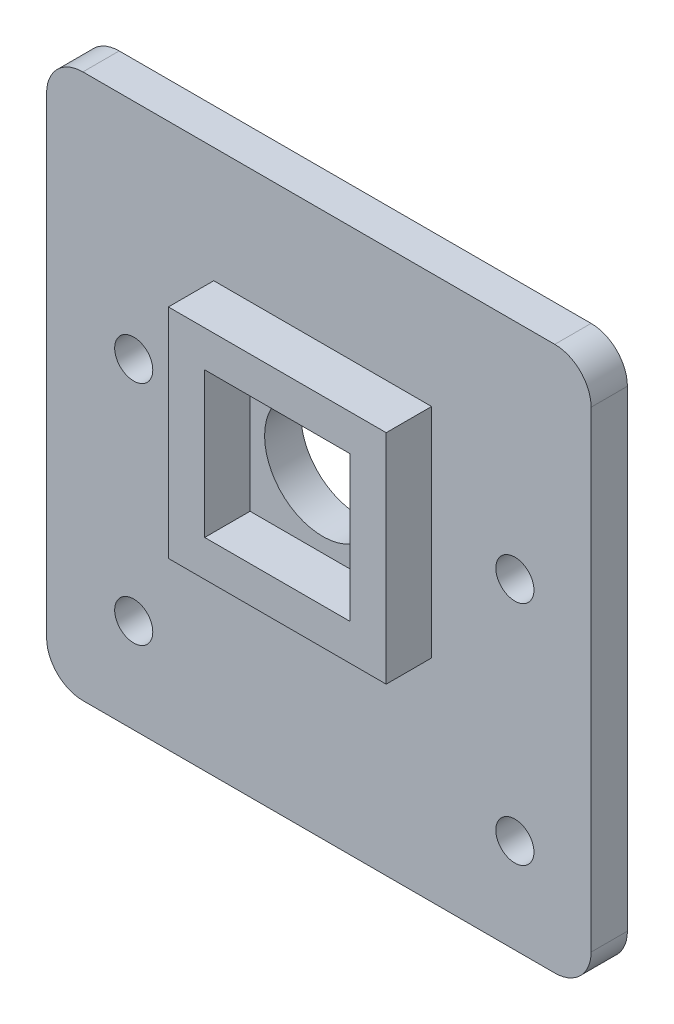
SolidWorks part; units mm, degrees
ref_plane "Front Plane" through (0, 0, 0) normal (0, 0, 1) x (1, 0, 0)
ref_plane "Top Plane" through (0, 0, 0) normal (0, 1, 0) x (1, 0, 0)
ref_plane "Right Plane" through (0, 0, 0) normal (1, 0, 0) x (0, 0, -1)
sketch "Sketch1" plane through (0, 0, 0) normal (0, 0, 1) x (1, 0, 0)
  line L1 (0, 0) -> (-30, 0)
  line L2 (0, 0) -> (0, 30)
  line L3 (0, 30) -> (-30, 30)
  line L4 (-30, 0) -> (-30, 30)
  dimension "D1" = 30
  dimension "D2" = 30
extrude "Boss-Extrude1" add sketch "Sketch1" along normal blind 2
sketch "Sketch2" plane through (0, 0, 2) normal (0, 0, 1) x (1, 0, 0)
  line L0 (-30, 30) -> (-30, 0) construction
  line L1 (-30, 0) -> (0, 0) construction
  line L2 (0, 0) -> (0, 30) construction
  circle A0 centre (-25.2, 5.199) radius 1.05
  circle A1 centre (-4.2, 5.199) radius 1.05
  circle A2 centre (-25.2, 17.699) radius 1.05
  circle A3 centre (-4.2, 17.699) radius 1.05
  dimension "D1" = 2.1
  dimension "D2" = 2.1
  dimension "D3" = 2.1
  dimension "D4" = 2.1
  dimension "D5" = 4.8
  dimension "D6" = 5.199
  dimension "D7" = 4.2
  dimension "D8" = 5.199
  dimension "D9" = 4.8
  dimension "D10" = 17.699
  dimension "D11" = 4.2
  dimension "D12" = 17.699
extrude "Cut-Extrude1" cut sketch "Sketch2" against normal blind 1.5
sketch "Sketch7" plane through (0, 0, 2) normal (0, 0, 1) x (1, 0, 0)
  line L0 (-30, 0) -> (0, 0) construction
  line L1 (-18.79, 21.64) -> (-10.79, 21.64)
  line L2 (-18.79, 21.64) -> (-18.79, 13.64)
  line L3 (-18.79, 13.64) -> (-10.79, 13.64)
  line L4 (-10.79, 21.64) -> (-10.79, 13.64)
  line L5 (-30, 30) -> (-30, 0) construction
  line L6 (-20.79, 23.64) -> (-8.79, 23.64)
  line L7 (-8.79, 23.64) -> (-8.79, 11.64)
  line L8 (-20.79, 11.64) -> (-8.79, 11.64)
  line L9 (-20.79, 23.64) -> (-20.79, 11.64)
  dimension "D1" = 8
  dimension "D2" = 8
  dimension "D3" = 13.64
  dimension "D4" = 11.21
  dimension "D5" = 2
extrude "Boss-Extrude4" add sketch "Sketch7" along normal blind 2.5
sketch "Sketch8" plane through (0, 0, 2) normal (0, 0, 1) x (1, 0, 0)
  line L0 (-30, 30) -> (-30, 0) construction
  line L4 (-18.79, 21.64) -> (-18.79, 13.64)
  line L5 (-18.79, 13.64) -> (-10.79, 13.64)
  line L6 (-10.79, 13.64) -> (-10.79, 21.64)
  line L7 (-10.79, 21.64) -> (-18.79, 21.64)
  line L8 (-18.79, 21.64) -> (-18.79, 13.64)
  line L9 (-18.79, 13.64) -> (-10.79, 13.64)
  line L10 (-10.79, 13.64) -> (-10.79, 21.64)
  line L11 (-10.79, 21.64) -> (-18.79, 21.64)
  dimension "D2" = 11.21
  dimension "D1" = 0
extrude "Cut-Extrude4" cut sketch "Sketch8" against normal blind 12.525
sketch "Sketch9" plane through (0, 0, 0) normal (0, 0, -1) x (-1, 0, 0)
  line L0 (18.79, 21.64) -> (18.79, 13.64) construction
  line L1 (10.79, 13.64) -> (10.79, 21.64) construction
  line L2 (10.79, 21.64) -> (18.79, 21.64) construction
  line L3 (18.79, 13.64) -> (10.79, 13.64) construction
  line L5 (10.79, 21.64) -> (18.79, 21.64)
  line L6 (10.79, 21.64) -> (10.79, 13.64)
  line L7 (10.79, 13.64) -> (18.79, 13.64)
  line L8 (18.79, 21.64) -> (18.79, 13.64)
  circle A0 centre (14.79, 17.64) radius 3.2
  dimension "D1" = 6.4
  dimension "D2" = 4
  dimension "D3" = 4
  dimension "D4" = 4
  dimension "D5" = 4
extrude "Boss-Extrude5" add sketch "Sketch9" against normal blind 2
fillet "Fillet1" radius 2 4 edges at (-30, 0, 1) (0, 0, 1) (0, 30, 1) (-30, 30, 1)
sketch "Sketch12" plane through (0, 0, 0) normal (0, 0, -1) x (-1, 0, 0)
  line L0 (5.5864, 22.6664) -> (5.5864, 20.7914) construction
  line L1 (5.5864, 27.3518) -> (5.5864, 28.4986) construction
  line L2 (6.0865, 26.4387) -> (6.1118, 26.4367)
  arc A0 (4.6128, 22.001) -> (4.5803, 21.522) centre (5.5864, 21.6942) ccw
  arc A1 (6.56, 22.001) -> (6.5925, 21.522) centre (5.5864, 21.6942) cw
  ellipse E0 centre (4.4059, 23.5084) end of major axis (4.9766, 24.428) minor radius 0.9345
  ellipse E1 centre (3.6535, 21.3068) end of major axis (3.0581, 22.1087) minor radius 0.5596 (3.7647, 20.5004) -> (2.9079, 21.7233) ccw
  ellipse E2 centre (7.5193, 21.3068) end of major axis (8.1147, 22.1087) minor radius 0.5596 (7.4081, 20.5004) -> (8.2649, 21.7233) cw
  ellipse E3 centre (6.7669, 23.5084) end of major axis (6.1962, 24.428) minor radius 0.9345
  spline S0 degree 3 poles (4.4661, 25.441) (4.0869, 25.541) (3.7007, 25.4582) (3.1996, 25.0648) (3.0254, 24.7187) (3.0272, 24.2593) knots 0 0 0 0 0.450332 0.550332 1 1 1 1
  spline S1 degree 2 poles (3.0272, 24.2593) (3.1067, 24.237) (3.1784, 24.2736) knots 0 0 0 1 1 1
  spline S2 degree 2 poles (4.4661, 25.441) (4.4803, 25.3569) (4.4192, 25.2998) knots 0 0 0 1 1 1
  spline S3 degree 2 poles (4.4192, 25.2998) (3.9027, 24.6623) (3.1784, 24.2736) knots 0 0 0 1 1 1
  spline S4 degree 3 poles (2.9201, 23.9593) (2.5666, 23.7576) (2.2127, 23.0851) (2.4728, 22.4495) (2.7037, 22.2258) knots 0 0 0 0 0.560262 1 1 1 1
  spline S5 degree 3 poles (2.9201, 23.9593) (2.9672, 23.98) (3.096, 23.8809) (3.1188, 23.716) (3.13, 23.6064) knots 0 0 0 0 0.260652 1 1 1 1
  spline S6 degree 3 poles (2.7037, 22.2258) (2.8317, 22.206) (2.9189, 22.3681) (2.9535, 22.4583) knots 0 0 0 0 1 1 1 1
  spline S7 degree 2 poles (3.13, 23.6064) (3.1595, 23.0141) (2.9535, 22.4583) knots 0 0 0 1 1 1
  spline S8 degree 2 poles (2.9079, 21.7233) (2.92, 20.8121) (3.7647, 20.5004) knots 0 0 0 1 1 1
  spline S9 degree 3 poles (4.6128, 22.001) (4.8153, 22.4679) (5.1862, 22.672) (5.5864, 22.6664) knots 0 0 0 0 0.49448 0.49448 0.49448 0.49448
  spline S10 degree 3 poles (4.5803, 21.522) (4.7766, 20.9634) (5.2258, 20.789) (5.5864, 20.7914) knots 0 0 0 0 0.451501 0.451501 0.451501 0.451501
  spline S11 degree 3 poles (4.5928, 20.1323) (4.6281, 20.267) (4.8215, 20.3612) (5.157, 20.4778) (5.2901, 20.4712) (5.5864, 20.4905) knots 0 0 0 0 0.33634 0.43634 1 1 1 1
  spline S12 degree 2 poles (4.5928, 20.1323) (4.5849, 20.0863) (4.6063, 20.0455) knots 0 0 0 1 1 1
  spline S13 degree 3 poles (4.6063, 20.0455) (4.7042, 19.8954) (4.8841, 19.7449) (5.1884, 19.6044) (5.375, 19.5496) (5.5864, 19.5559) knots 0 0 0 0 0.397504 0.497504 1 1 1 1
  spline S14 degree 3 poles (5.5864, 25.6921) (5.2761, 25.7126) (4.8033, 25.5166) (4.6599, 25.2139) knots 0 0 0 0 1 1 1 1
  spline S15 degree 2 poles (4.6599, 25.2139) (4.6332, 25.1127) (4.6746, 25.016) knots 0 0 0 1 1 1
  spline S16 degree 3 poles (4.6746, 25.016) (4.7203, 24.8882) (5.0275, 24.6755) (5.3683, 24.6145) (5.5864, 24.6098) knots 0 0 0 0 0.380769 1 1 1 1
  spline S17 degree 3 poles (6.4982, 25.016) (6.4525, 24.8882) (6.1453, 24.6755) (5.8045, 24.6145) (5.5864, 24.6098) knots 0 0 0 0 0.380769 1 1 1 1
  spline S18 degree 2 poles (6.5129, 25.2139) (6.5396, 25.1127) (6.4982, 25.016) knots 0 0 0 1 1 1
  spline S19 degree 3 poles (5.5864, 25.6921) (5.8967, 25.7126) (6.3695, 25.5166) (6.5129, 25.2139) knots 0 0 0 0 1 1 1 1
  spline S20 degree 3 poles (6.5665, 20.0455) (6.4686, 19.8954) (6.2887, 19.7449) (5.9844, 19.6044) (5.7978, 19.5496) (5.5864, 19.5559) knots 0 0 0 0 0.397504 0.497504 1 1 1 1
  spline S21 degree 2 poles (6.58, 20.1323) (6.5878, 20.0863) (6.5665, 20.0455) knots 0 0 0 1 1 1
  spline S22 degree 3 poles (6.58, 20.1323) (6.5447, 20.267) (6.3513, 20.3612) (6.0158, 20.4778) (5.8826, 20.4712) (5.5864, 20.4905) knots 0 0 0 0 0.33634 0.43634 1 1 1 1
  spline S23 degree 3 poles (6.5925, 21.522) (6.3962, 20.9634) (5.947, 20.789) (5.5864, 20.7914) knots 0 0 0 0 0.451501 0.451501 0.451501 0.451501
  spline S24 degree 3 poles (6.56, 22.001) (6.3575, 22.4679) (5.9866, 22.672) (5.5864, 22.6664) knots 0 0 0 0 0.49448 0.49448 0.49448 0.49448
  spline S25 degree 2 poles (8.2649, 21.7233) (8.2528, 20.8121) (7.4081, 20.5004) knots 0 0 0 1 1 1
  spline S26 degree 2 poles (8.0428, 23.6064) (8.0133, 23.0141) (8.2193, 22.4583) knots 0 0 0 1 1 1
  spline S27 degree 3 poles (8.4691, 22.2258) (8.3411, 22.206) (8.2539, 22.3681) (8.2193, 22.4583) knots 0 0 0 0 1 1 1 1
  spline S28 degree 3 poles (8.2526, 23.9593) (8.2056, 23.98) (8.0768, 23.8809) (8.054, 23.716) (8.0428, 23.6064) knots 0 0 0 0 0.260652 1 1 1 1
  spline S29 degree 3 poles (8.2526, 23.9593) (8.6062, 23.7576) (8.9601, 23.0851) (8.7, 22.4495) (8.4691, 22.2258) knots 0 0 0 0 0.560262 1 1 1 1
  spline S30 degree 2 poles (6.7536, 25.2998) (7.2701, 24.6623) (7.9944, 24.2736) knots 0 0 0 1 1 1
  spline S31 degree 2 poles (6.7067, 25.441) (6.6925, 25.3569) (6.7536, 25.2998) knots 0 0 0 1 1 1
  spline S32 degree 2 poles (8.1456, 24.2593) (8.066, 24.237) (7.9944, 24.2736) knots 0 0 0 1 1 1
  spline S33 degree 3 poles (6.7067, 25.441) (7.0859, 25.541) (7.4721, 25.4582) (7.9732, 25.0648) (8.1474, 24.7187) (8.1456, 24.2593) knots 0 0 0 0 0.450332 0.550332 1 1 1 1
  spline S34 degree 2 poles (4.4594, 19.7714) (4.9124, 19.2698) (5.5864, 19.2771) knots 0 0 0 1 1 1
  spline S35 degree 2 poles (4.4594, 19.7714) (3.9767, 19.9521) (3.5736, 20.2731) knots 0 0 0 1 1 1
  spline S36 degree 2 poles (3.5736, 20.2731) (2.7752, 20.6024) (2.6468, 21.4613) knots 0 0 0 1 1 1
  spline S37 degree 2 poles (2.6468, 21.4613) (2.497, 21.7547) (2.4415, 22.0792) knots 0 0 0 1 1 1
  spline S38 degree 3 poles (2.4415, 22.0792) (2.2134, 22.3349) (1.9009, 23.1138) (2.2811, 23.8445) (2.672, 24.1298) knots 0 0 0 0 0.443044 1 1 1 1
  spline S39 degree 3 poles (2.672, 24.1298) (2.6941, 24.185) (2.7152, 24.2148) (2.7442, 24.2537) knots 0 0 0 0 1 1 1 1
  spline S40 degree 2 poles (2.7442, 24.2537) (2.7442, 25.2242) (3.5461, 25.6386) knots 0 0 0 1 1 1
  spline S41 degree 2 poles (3.5461, 25.6386) (3.3119, 25.653) (3.2366, 25.8676) knots 0 0 0 1 1 1
  spline S42 degree 3 poles (3.2366, 25.8676) (3.0982, 25.9236) (2.9587, 25.9761) (2.9535, 26.1566) knots 0 0 0 0 1 1 1 1
  spline S43 degree 3 poles (2.9535, 26.1566) (2.7484, 26.2735) (2.727, 26.2895) (2.7122, 26.4944) knots 0 0 0 0 1 1 1 1
  spline S44 degree 2 poles (2.7122, 26.4944) (2.5063, 26.6143) (2.572, 26.811) knots 0 0 0 1 1 1
  spline S45 degree 3 poles (2.572, 26.811) (2.4868, 26.9313) (2.3857, 26.9889) (2.4773, 27.1499) knots 0 0 0 0 1 1 1 1
  spline S46 degree 2 poles (2.4773, 27.1499) (2.2981, 27.3347) (2.4691, 27.5085) knots 0 0 0 1 1 1
  spline S47 degree 3 poles (2.4691, 27.5085) (2.3555, 27.6167) (2.4238, 27.8568) (2.5808, 27.8736) knots 0 0 0 0 1 1 1 1
  spline S48 degree 2 poles (2.5808, 27.8736) (2.662, 27.8906) (2.7442, 27.8798) knots 0 0 0 1 1 1
  spline S49 degree 2 poles (2.7442, 27.8798) (2.8263, 28.0205) (2.9934, 28.008) knots 0 0 0 1 1 1
  spline S50 degree 2 poles (2.9934, 28.008) (3.0748, 28.0275) (3.1571, 28.0125) knots 0 0 0 1 1 1
  spline S51 degree 3 poles (3.1571, 28.0125) (3.2116, 28.1159) (3.346, 28.1028) (3.4398, 28.0895) knots 0 0 0 0 1 1 1 1
  spline S52 degree 3 poles (3.4398, 28.0895) (3.5458, 28.1764) (3.5906, 28.2096) (3.8177, 28.1351) knots 0 0 0 0 1 1 1 1
  spline S53 degree 2 poles (3.8177, 28.1351) (4.0116, 28.26) (4.206, 28.1192) knots 0 0 0 1 1 1
  spline S54 degree 2 poles (4.206, 28.1192) (4.3888, 28.1919) (4.5474, 28.0479) knots 0 0 0 1 1 1
  spline S55 degree 3 poles (4.5474, 28.0479) (4.7019, 28.1379) (4.8375, 28.0016) (4.9189, 27.9015) knots 0 0 0 0 1 1 1 1
  spline S56 degree 3 poles (4.9189, 27.9015) (4.9882, 27.9113) (5.0998, 27.8815) (5.2348, 27.758) (5.4564, 27.5411) (5.5864, 27.0972) knots 0 0 0 0 0.0926 0.1926 1 1 1 1
  spline S57 degree 2 poles (6.7134, 19.7714) (6.2604, 19.2698) (5.5864, 19.2771) knots 0 0 0 1 1 1
  spline S58 degree 2 poles (6.7134, 19.7714) (7.1961, 19.9521) (7.5992, 20.2731) knots 0 0 0 1 1 1
  spline S59 degree 2 poles (7.5992, 20.2731) (8.3976, 20.6024) (8.526, 21.4613) knots 0 0 0 1 1 1
  spline S60 degree 2 poles (8.526, 21.4613) (8.6758, 21.7547) (8.7313, 22.0792) knots 0 0 0 1 1 1
  spline S61 degree 3 poles (8.7313, 22.0792) (8.9594, 22.3349) (9.2719, 23.1138) (8.8917, 23.8445) (8.5008, 24.1298) knots 0 0 0 0 0.443044 1 1 1 1
  spline S62 degree 3 poles (8.5008, 24.1298) (8.4787, 24.185) (8.4576, 24.2148) (8.4286, 24.2537) knots 0 0 0 0 1 1 1 1
  spline S63 degree 2 poles (8.4286, 24.2537) (8.4286, 25.2242) (7.6267, 25.6386) knots 0 0 0 1 1 1
  spline S64 degree 2 poles (7.6267, 25.6386) (7.8609, 25.653) (7.9362, 25.8676) knots 0 0 0 1 1 1
  spline S65 degree 3 poles (6.2539, 27.9015) (6.1846, 27.9113) (6.073, 27.8815) (5.938, 27.758) (5.7164, 27.5411) (5.5864, 27.0972) knots 0 0 0 0 0.0926 0.1926 1 1 1 1
  spline S66 degree 3 poles (6.6254, 28.0479) (6.4709, 28.1379) (6.3353, 28.0016) (6.2539, 27.9015) knots 0 0 0 0 1 1 1 1
  spline S67 degree 2 poles (6.9668, 28.1192) (6.784, 28.1919) (6.6254, 28.0479) knots 0 0 0 1 1 1
  spline S68 degree 2 poles (7.3551, 28.1351) (7.1612, 28.26) (6.9668, 28.1192) knots 0 0 0 1 1 1
  spline S69 degree 3 poles (7.733, 28.0895) (7.627, 28.1764) (7.5822, 28.2096) (7.3551, 28.1351) knots 0 0 0 0 1 1 1 1
  spline S70 degree 3 poles (8.0157, 28.0125) (7.9612, 28.1159) (7.8268, 28.1028) (7.733, 28.0895) knots 0 0 0 0 1 1 1 1
  spline S71 degree 2 poles (8.1794, 28.008) (8.098, 28.0275) (8.0157, 28.0125) knots 0 0 0 1 1 1
  spline S72 degree 2 poles (8.4286, 27.8798) (8.3465, 28.0205) (8.1794, 28.008) knots 0 0 0 1 1 1
  spline S73 degree 2 poles (8.592, 27.8736) (8.5108, 27.8906) (8.4286, 27.8798) knots 0 0 0 1 1 1
  spline S74 degree 3 poles (8.7037, 27.5085) (8.8173, 27.6167) (8.749, 27.8568) (8.592, 27.8736) knots 0 0 0 0 1 1 1 1
  spline S75 degree 2 poles (8.6954, 27.1499) (8.8747, 27.3347) (8.7037, 27.5085) knots 0 0 0 1 1 1
  spline S76 degree 3 poles (8.6008, 26.811) (8.686, 26.9313) (8.7871, 26.9889) (8.6954, 27.1499) knots 0 0 0 0 1 1 1 1
  spline S77 degree 2 poles (8.4606, 26.4944) (8.6665, 26.6143) (8.6008, 26.811) knots 0 0 0 1 1 1
  spline S78 degree 3 poles (8.2193, 26.1566) (8.4243, 26.2735) (8.4458, 26.2895) (8.4606, 26.4944) knots 0 0 0 0 1 1 1 1
  spline S79 degree 3 poles (7.9362, 25.8676) (8.0746, 25.9236) (8.2141, 25.9761) (8.2193, 26.1566) knots 0 0 0 0 1 1 1 1
  spline S80 degree 2 poles (3.8083, 25.7218) (3.8837, 25.7494) (3.9286, 25.8155) knots 0 0 0 1 1 1
  spline S81 degree 2 poles (3.9286, 25.8155) (3.6928, 25.8262) (3.4711, 25.9053) knots 0 0 0 1 1 1
  spline S82 degree 2 poles (3.4711, 25.9053) (3.5527, 25.9177) (3.598, 25.9861) knots 0 0 0 1 1 1
  spline S83 degree 2 poles (3.598, 25.9861) (3.3734, 26.0212) (3.1858, 26.1477) knots 0 0 0 1 1 1
  spline S84 degree 2 poles (3.1858, 26.1477) (3.2778, 26.1432) (3.348, 26.1998) knots 0 0 0 1 1 1
  spline S85 degree 2 poles (3.348, 26.1998) (3.1237, 26.2775) (2.9481, 26.4357) knots 0 0 0 1 1 1
  spline S86 degree 2 poles (2.9481, 26.4357) (3.0367, 26.42) (3.1125, 26.4644) knots 0 0 0 1 1 1
  spline S87 degree 2 poles (3.1125, 26.4644) (2.9393, 26.5748) (2.7961, 26.7218) knots 0 0 0 1 1 1
  spline S88 degree 2 poles (2.7961, 26.7218) (2.8867, 26.7091) (2.9667, 26.7489) knots 0 0 0 1 1 1
  spline S89 degree 2 poles (2.9667, 26.7489) (2.7958, 26.8643) (2.6811, 27.0342) knots 0 0 0 1 1 1
  spline S90 degree 2 poles (2.6811, 27.0342) (2.787, 26.9982) (2.8848, 27.0455) knots 0 0 0 1 1 1
  spline S91 degree 2 poles (2.8848, 27.0455) (2.7302, 27.166) (2.6265, 27.3307) knots 0 0 0 1 1 1
  spline S92 degree 2 poles (2.6265, 27.3307) (2.716, 27.3137) (2.8058, 27.3241) knots 0 0 0 1 1 1
  spline S93 degree 2 poles (2.8058, 27.3241) (2.7639, 27.5101) (2.6322, 27.6484) knots 0 0 0 1 1 1
  spline S94 degree 2 poles (2.6322, 27.6484) (2.8417, 27.6387) (3.0506, 27.6578) knots 0 0 0 1 1 1
  spline S95 degree 2 poles (3.0506, 27.6578) (3.0066, 27.7219) (2.9441, 27.7683) knots 0 0 0 1 1 1
  spline S96 degree 2 poles (2.9441, 27.7683) (3.1707, 27.8192) (3.3933, 27.7251) knots 0 0 0 1 1 1
  spline S97 degree 3 poles (3.3933, 27.7251) (3.4746, 27.7603) (3.3577, 27.8587) (3.3251, 27.8635) knots 0 0 0 0 1 1 1 1
  spline S98 degree 2 poles (3.3251, 27.8635) (3.5263, 27.872) (3.7092, 27.7775) knots 0 0 0 1 1 1
  spline S99 degree 3 poles (3.7092, 27.7775) (3.7526, 27.8209) (3.6934, 27.869) (3.6153, 27.9407) knots 0 0 0 0 1 1 1 1
  spline S100 degree 2 poles (3.6153, 27.9407) (3.8351, 27.9183) (4.0132, 27.7914) knots 0 0 0 1 1 1
  spline S101 degree 3 poles (4.0132, 27.7914) (4.083, 27.8273) (4.0103, 27.9269) (3.9768, 27.9527) knots 0 0 0 0 1 1 1 1
  spline S102 degree 2 poles (3.9768, 27.9527) (4.1705, 27.8956) (4.3129, 27.7541) knots 0 0 0 1 1 1
  spline S103 degree 2 poles (4.3129, 27.7541) (4.3882, 27.8249) (4.3227, 27.9051) knots 0 0 0 1 1 1
  spline S104 degree 2 poles (4.3227, 27.9051) (4.479, 27.8277) (4.5803, 27.6879) knots 0 0 0 1 1 1
  spline S105 degree 3 poles (4.5803, 27.6879) (4.6378, 27.7085) (4.6585, 27.734) (4.6358, 27.8444) knots 0 0 0 0 1 1 1 1
  spline S106 degree 2 poles (4.6358, 27.8444) (4.8084, 27.7187) (4.9236, 27.5388) knots 0 0 0 1 1 1
  spline S107 degree 2 poles (4.9236, 27.5388) (4.9685, 27.5954) (4.9712, 27.6682) knots 0 0 0 1 1 1
  spline S108 degree 3 poles (4.9712, 27.6682) (5.106, 27.5678) (5.2785, 27.2989) (5.4306, 26.8212) (5.3198, 26.5497) (5.0863, 26.4387) knots 0 0 0 0 0.370607 0.596988 1 1 1 1
  spline S109 degree 1 poles (5.0863, 26.4387) (5.061, 26.4367) knots 0 0 1 1
  spline S110 degree 2 poles (5.061, 26.4367) (4.2873, 27.0507) (3.348, 27.3518) knots 0 0 0 1 1 1
  spline S111 degree 3 poles (3.348, 27.3518) (3.7184, 27.1581) (4.2685, 26.8666) (4.7453, 26.4699) (4.9377, 26.2658) knots 0 0 0 0 0.517858 1 1 1 1
  spline S112 degree 3 poles (4.9377, 26.2658) (4.9024, 26.1408) (4.7187, 25.775) (4.1062, 25.6906) (3.8083, 25.7218) knots 0 0 0 0 0.232285 1 1 1 1
  spline S113 degree 3 poles (6.2351, 26.2658) (6.2704, 26.1408) (6.4541, 25.775) (7.0666, 25.6906) (7.3645, 25.7218) knots 0 0 0 0 0.232285 1 1 1 1
  spline S114 degree 2 poles (7.3645, 25.7218) (7.2891, 25.7494) (7.2442, 25.8155) knots 0 0 0 1 1 1
  spline S115 degree 2 poles (7.2442, 25.8155) (7.48, 25.8262) (7.7017, 25.9053) knots 0 0 0 1 1 1
  spline S116 degree 2 poles (7.5748, 25.9861) (7.7994, 26.0212) (7.987, 26.1477) knots 0 0 0 1 1 1
  spline S117 degree 2 poles (7.987, 26.1477) (7.895, 26.1432) (7.8248, 26.1998) knots 0 0 0 1 1 1
  spline S118 degree 2 poles (7.8248, 26.1998) (8.0491, 26.2775) (8.2247, 26.4357) knots 0 0 0 1 1 1
  spline S119 degree 2 poles (8.2247, 26.4357) (8.1361, 26.42) (8.0603, 26.4644) knots 0 0 0 1 1 1
  spline S120 degree 2 poles (8.0603, 26.4644) (8.2335, 26.5748) (8.3767, 26.7218) knots 0 0 0 1 1 1
  spline S121 degree 2 poles (8.3767, 26.7218) (8.2861, 26.7091) (8.2061, 26.7489) knots 0 0 0 1 1 1
  spline S122 degree 2 poles (8.2061, 26.7489) (8.377, 26.8643) (8.4917, 27.0342) knots 0 0 0 1 1 1
  spline S123 degree 2 poles (8.4917, 27.0342) (8.3858, 26.9982) (8.288, 27.0455) knots 0 0 0 1 1 1
  spline S124 degree 2 poles (8.288, 27.0455) (8.4426, 27.166) (8.5463, 27.3307) knots 0 0 0 1 1 1
  spline S125 degree 2 poles (8.5463, 27.3307) (8.4568, 27.3137) (8.367, 27.3241) knots 0 0 0 1 1 1
  spline S126 degree 2 poles (8.367, 27.3241) (8.4089, 27.5101) (8.5406, 27.6484) knots 0 0 0 1 1 1
  spline S127 degree 2 poles (8.5406, 27.6484) (8.3311, 27.6387) (8.1222, 27.6578) knots 0 0 0 1 1 1
  spline S128 degree 2 poles (8.1222, 27.6578) (8.1662, 27.7219) (8.2287, 27.7683) knots 0 0 0 1 1 1
  spline S129 degree 2 poles (8.2287, 27.7683) (8.002, 27.8192) (7.7795, 27.7251) knots 0 0 0 1 1 1
  spline S130 degree 3 poles (7.7795, 27.7251) (7.6982, 27.7603) (7.8151, 27.8587) (7.8477, 27.8635) knots 0 0 0 0 1 1 1 1
  spline S131 degree 3 poles (7.4636, 27.7775) (7.4202, 27.8209) (7.4794, 27.869) (7.5575, 27.9407) knots 0 0 0 0 1 1 1 1
  spline S132 degree 2 poles (7.8477, 27.8635) (7.6465, 27.872) (7.4636, 27.7775) knots 0 0 0 1 1 1
  spline S133 degree 3 poles (7.1596, 27.7914) (7.0898, 27.8273) (7.1625, 27.9269) (7.196, 27.9527) knots 0 0 0 0 1 1 1 1
  spline S134 degree 2 poles (7.5575, 27.9407) (7.3377, 27.9183) (7.1596, 27.7914) knots 0 0 0 1 1 1
  spline S135 degree 2 poles (6.8599, 27.7541) (6.7846, 27.8249) (6.8501, 27.9051) knots 0 0 0 1 1 1
  spline S136 degree 2 poles (7.196, 27.9527) (7.0023, 27.8956) (6.8599, 27.7541) knots 0 0 0 1 1 1
  spline S137 degree 2 poles (6.8501, 27.9051) (6.6938, 27.8277) (6.5925, 27.6879) knots 0 0 0 1 1 1
  spline S138 degree 3 poles (6.5925, 27.6879) (6.535, 27.7085) (6.5143, 27.734) (6.537, 27.8444) knots 0 0 0 0 1 1 1 1
  spline S139 degree 2 poles (6.537, 27.8444) (6.3644, 27.7187) (6.2491, 27.5388) knots 0 0 0 1 1 1
  spline S140 degree 2 poles (6.2491, 27.5388) (6.2043, 27.5954) (6.2016, 27.6682) knots 0 0 0 1 1 1
  spline S141 degree 3 poles (6.2016, 27.6682) (6.0668, 27.5678) (5.8943, 27.2989) (5.7422, 26.8212) (5.853, 26.5497) (6.0865, 26.4387) knots 0 0 0 0 0.370607 0.596988 1 1 1 1
  spline S142 degree 3 poles (7.8248, 27.3518) (7.4544, 27.1581) (6.9043, 26.8666) (6.4275, 26.4699) (6.2351, 26.2658) knots 0 0 0 0 0.517858 1 1 1 1
  spline S143 degree 2 poles (6.1118, 26.4367) (6.8855, 27.0507) (7.8248, 27.3518) knots 0 0 0 1 1 1
  spline S144 degree 2 poles (7.7017, 25.9053) (7.6201, 25.9177) (7.5748, 25.9861) knots 0 0 0 1 1 1
extrude "Cut-Extrude6" cut sketch "Sketch12" against normal blind 1
